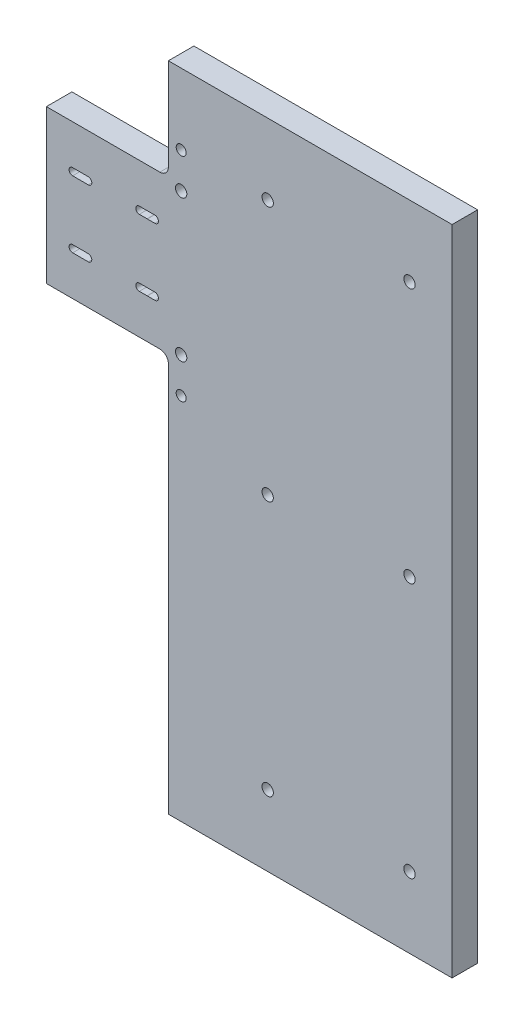
SolidWorks part; units mm, degrees
ref_plane "Front Plane" through (0, 0, 0) normal (0, 0, 1) x (1, 0, 0)
ref_plane "Top Plane" through (0, 0, 0) normal (0, 1, 0) x (1, 0, 0)
ref_plane "Right Plane" through (0, 0, 0) normal (1, 0, 0) x (0, 0, -1)
sketch "Sketch1" plane through (0, 0, 0) normal (0, 0, 1) x (1, 0, 0)
  line L1 (-100, 230) -> (100, 230)
  line L2 (-100, 230) -> (-100, -230)
  line L3 (-100, -230) -> (100, -230)
  line L4 (100, 230) -> (100, -230)
  line L5 (-100, 230) -> (100, -230) construction
  line L6 (-100, -230) -> (100, 230) construction
  point P0 (0, 0)
  dimension "D1" = 460
  dimension "D2" = 200
extrude "Boss-Extrude1" add sketch "Sketch1" along normal blind 18
hole_wizard "Otwory ustalające Ø8.0mm1" positions "Szkic2" profile "Szkic1" hole size "Ø8.0" standard "ISO" end condition through all
sketch "Szkic2" plane through (0, 0, 0) normal (0, 0, -1) x (-1, 0, 0)
  line L0 (-100, 230) -> (100, 230) construction
  line L1 (-100, -230) -> (-100, 230) construction
  line L2 (100, 230) -> (100, -230) construction
  line L3 (100, -230) -> (-100, -230) construction
  point P0 (-70, 180)
  point P2 (-70, 0)
  point P4 (-70, -180)
  point P6 (30, -180)
  point P8 (30, 0)
  point P10 (30, 180)
  dimension "D1" = 50
  dimension "D2" = 30
  dimension "D3" = 70
  dimension "D4" = 50
  dimension "D5" = 180
  dimension "D6" = 50
  dimension "D7" = 180
  dimension "D8" = 50
  dimension "D9" = 30
  dimension "D10" = 30
  dimension "D11" = 70
  dimension "D12" = 70
sketch "Szkic1" plane through (70, 180, 0) normal (1, 0, 0) x (0, 1, 0)
  line L0 (0, 0) -> (0, 18)
  line L1 (0, 18) -> (4, 18)
  line L2 (4, 18) -> (4, 0)
  line L5 (4, 0) -> (0, 0)
  line L11 (0, -6.35) -> (0, 107.95) construction
  dimension "Średnica otworu na wylot" = 8
  dimension "Głębokość otworu na wylot" = 18
hole_wizard "Otwór Ø7.0 (7)1" positions "Szkic4" profile "Szkic3" hole size "Ø7.0" standard "ISO" end condition through all
sketch "Szkic4" plane through (0, 0, 18) normal (0, 0, 1) x (1, 0, 0)
  point P0 (-91, 180)
  point P3 (-91, 30)
sketch "Szkic3" plane through (-91, 180, 18) normal (1, 0, 0) x (0, -1, 0)
  line L0 (0, 0) -> (0, 18)
  line L1 (0, 18) -> (3.5, 18)
  line L2 (3.5, 18) -> (3.5, 0)
  line L5 (3.5, 0) -> (0, 0)
  line L11 (0, -6.35) -> (0, 107.95) construction
  dimension "Średnica otworu na wylot" = 7
  dimension "Głębokość otworu na wylot" = 18
hole_wizard "Otwór Ø5.0 (5)1" positions "Szkic6" profile "Szkic5" hole size "Ø5.0" standard "ISO"
sketch "Szkic6" plane through (0, -230, 0) normal (0, -1, 0) x (-1, 0, 0)
  line L0 (100, 0) -> (-100, 0) construction
  line L1 (-100, -18) -> (-100, 0) construction
  line L2 (100, -18) -> (100, 0) construction
  point P0 (50, -9)
  point P2 (-50, -9)
  dimension "D1" = 9
  dimension "D2" = 9
  dimension "D3" = 50
  dimension "D4" = 50
sketch "Szkic5" plane through (-50, -230, 9) normal (1, 0, 0) x (0, 0, -1)
  line L0 (0, 0) -> (0, 46.5022)
  line L1 (0, 46.5022) -> (2.5, 45)
  line L2 (2.5, 45) -> (2.5, 0)
  line L5 (2.5, 0) -> (0, 0)
  line L10 (0, 46.5022) -> (-2.5, 45) construction
  line L11 (0, -6.35) -> (0, 107.95) construction
  dimension "Średnica otworu" = 5
  dimension "Głębokość otworu" = 45
  dimension "Kąt wiertła" = 118
sketch "Szkic8" plane through (0, 0, 18) normal (0, 0, 1) x (1, 0, 0)
  line L0 (-100, 230) -> (-100, -230) construction
  line L1 (-100, 165) -> (-100, 45)
  line L2 (-106, 159) -> (-186, 159)
  line L3 (-106, 51) -> (-186, 51)
  line L4 (-186, 51) -> (-186, 159)
  line L5 (100, 230) -> (-100, 230) construction
  arc A0 (-100, 165) -> (-106, 159) centre (-106, 165) cw
  arc A1 (-100, 45) -> (-106, 51) centre (-106, 45) ccw
  dimension "D1" = 6
  dimension "D2" = 6
  dimension "D3" = 71
  dimension "D4" = 120
  dimension "D5" = 80
extrude "Dodanie-wyciągnięcie1" add sketch "Szkic8" against normal blind 18
hole_wizard "Otwór Ø5.0 (5)2" positions "Szkic10" profile "Szkic9" hole size "Ø5.0" standard "ISO" end condition through all
sketch "Szkic10" plane through (0, 0, 18) normal (0, 0, 1) x (1, 0, 0)
  point P0 (-161.9284, 128.5)
  point P2 (-114.9284, 128.4982)
  point P4 (-114.9284, 81.4982)
  point P6 (-161.9284, 81.5)
sketch "Szkic9" plane through (-161.9284, 128.5, 18) normal (1, 0, 0) x (0, -1, 0)
  line L0 (0, 0) -> (0, 18)
  line L1 (0, 18) -> (2.5, 18)
  line L2 (2.5, 18) -> (2.5, 0)
  line L5 (2.5, 0) -> (0, 0)
  line L11 (0, -6.35) -> (0, 107.95) construction
  dimension "Średnica otworu na wylot" = 5
  dimension "Głębokość otworu na wylot" = 18
sketch "Szkic11" plane through (0, 0, 0) normal (0, 0, -1) x (-1, 0, 0)
  line L0 (109.5, 128.5) -> (120.5, 128.5) construction
  line L1 (109.5, 131) -> (120.5, 131)
  line L2 (109.5, 126) -> (120.5, 126)
  line L3 (156.5, 128.5) -> (167.5, 128.5) construction
  line L4 (156.5, 131) -> (167.5, 131)
  line L5 (156.5, 126) -> (167.5, 126)
  line L6 (109.5, 81.5) -> (120.5, 81.5) construction
  line L7 (109.5, 84) -> (120.5, 84)
  line L8 (109.5, 79) -> (120.5, 79)
  line L9 (156.5, 81.5) -> (167.5, 81.5) construction
  line L10 (156.5, 84) -> (167.5, 84)
  line L11 (156.5, 79) -> (167.5, 79)
  line L13 (186, 159) -> (186, 51) construction
  line L14 (186, 51) -> (106, 51) construction
  arc A0 (109.5, 131) -> (109.5, 126) centre (109.5, 128.5) ccw
  arc A1 (120.5, 126) -> (120.5, 131) centre (120.5, 128.5) ccw
  arc A2 (156.5, 131) -> (156.5, 126) centre (156.5, 128.5) ccw
  arc A3 (167.5, 126) -> (167.5, 131) centre (167.5, 128.5) ccw
  arc A4 (109.5, 84) -> (109.5, 79) centre (109.5, 81.5) ccw
  arc A5 (120.5, 79) -> (120.5, 84) centre (120.5, 81.5) ccw
  arc A6 (156.5, 84) -> (156.5, 79) centre (156.5, 81.5) ccw
  arc A7 (167.5, 79) -> (167.5, 84) centre (167.5, 81.5) ccw
  point P2 (115, 128.5)
  point P7 (162, 128.5)
  point P14 (115, 81.5)
  point P21 (162, 81.5)
  dimension "D1" = 2.5
  dimension "D2" = 2.5
  dimension "D3" = 2.5
  dimension "D4" = 2.5
  dimension "D6" = 11
  dimension "D13" = 24
  dimension "D5" = 11
  dimension "D7" = 11
  dimension "D8" = 11
  dimension "D9" = 36
  dimension "D10" = 36
  dimension "D11" = 47
  dimension "D12" = 47
  dimension "D14" = 30.5
extrude "Wytnij-wyciągnięcie1" cut sketch "Szkic11" against normal through all contours L2 A1 L1 A0 | L5 A3 L4 A2 | L11 A7 L10 A6 | L8 A5 L7 A4
hole_wizard "Otwór Ø8.0 (8)1" positions "Szkic13" profile "Szkic12" hole size "Ø8.0" standard "ISO"
sketch "Szkic13" plane through (0, 0, 18) normal (0, 0, 1) x (1, 0, 0)
  point P0 (-91, 155)
  point P2 (-91, 55)
sketch "Szkic12" plane through (-91, 155, 18) normal (1, 0, 0) x (0, -1, 0)
  line L0 (0, 0) -> (0, 17.4034)
  line L1 (0, 17.4034) -> (4, 15)
  line L2 (4, 15) -> (4, 0)
  line L5 (4, 0) -> (0, 0)
  line L10 (0, 17.4034) -> (-4, 15) construction
  line L11 (0, -6.35) -> (0, 107.95) construction
  dimension "Średnica otworu" = 8
  dimension "Głębokość otworu" = 15
  dimension "Kąt wiertła" = 118
hole_wizard "Otwór Ø8.0 (8)2" positions "Szkic15" profile "Szkic14" hole size "Ø8.0" standard "ISO"
sketch "Szkic15" plane through (0, -230, 0) normal (0, -1, 0) x (-1, 0, 0)
  line L0 (100, -18) -> (-100, -18) construction
  line L1 (-100, -18) -> (-100, 0) construction
  point P0 (0, -9)
  dimension "D1" = 9
  dimension "D2" = 100
sketch "Szkic14" plane through (0, -230, 9) normal (1, 0, 0) x (0, 0, -1)
  line L0 (0, 0) -> (0, 24.4034)
  line L1 (0, 24.4034) -> (4, 22)
  line L2 (4, 22) -> (4, 0)
  line L5 (4, 0) -> (0, 0)
  line L10 (0, 24.4034) -> (-4, 22) construction
  line L11 (0, -6.35) -> (0, 107.95) construction
  dimension "Średnica otworu" = 8
  dimension "Głębokość otworu" = 22
  dimension "Kąt wiertła" = 118
